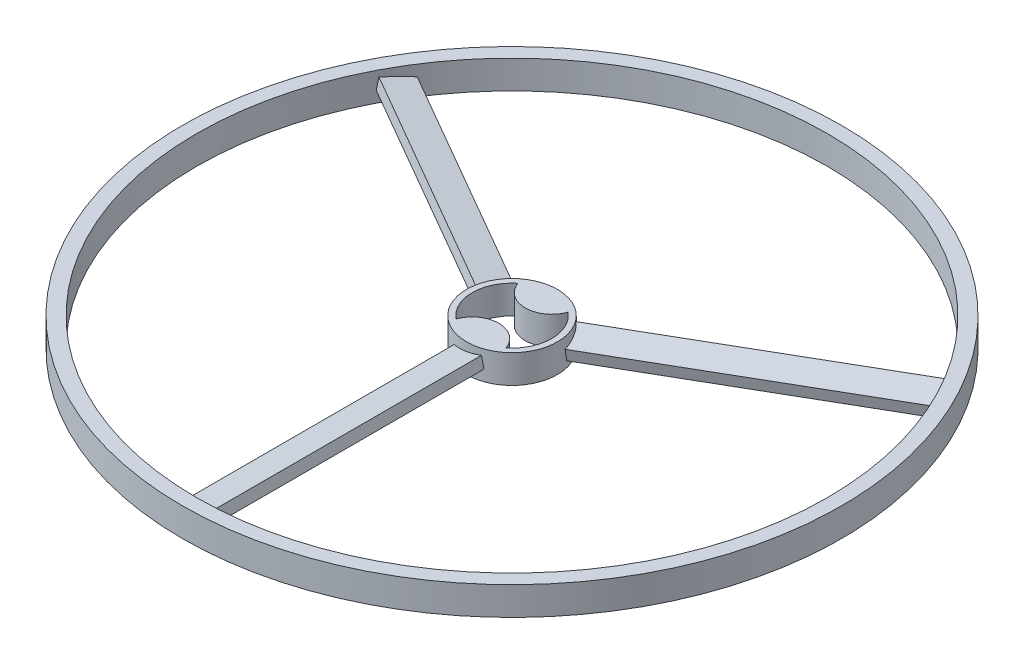
SolidWorks part; units mm, degrees
ref_plane "정면" through (0, 0, 0) normal (0, 0, 1) x (1, 0, 0)
ref_plane "윗면" through (0, 0, 0) normal (0, 1, 0) x (1, 0, 0)
ref_plane "우측면" through (0, 0, 0) normal (1, 0, 0) x (0, 0, -1)
sketch "Sketch1" plane through (0, 0, 0) normal (0, 0, 1) x (1, 0, 0)
  line L0 (-8, 0) -> (8, 0) construction
  line L1 (0, -2.5) -> (0, 2.5) construction
  line L2 (0, 0) -> (2.462, 0.4341) construction
  line L3 (2.2884, 1.4189) -> (2.6357, -0.5507)
  line L4 (2.6357, -0.5507) -> (-2.2884, -1.4189)
  line L5 (-2.2884, -1.4189) -> (-2.6357, 0.5507)
  line L6 (-2.6357, 0.5507) -> (2.2884, 1.4189)
  point P10 (2.462, 0.4341)
  dimension "D1" = 5
  dimension "D2" = 16
  dimension "D3" = 10
  dimension "D4" = 2
  dimension "D5" = 5
  dimension "D6" = 2.5
sketch "Sketch2" plane through (0, 0, 0) normal (0, 1, 0) x (1, 0, 0)
  line L0 (0, 0.9727) -> (0, -14.097) construction
  line L1 (0, 0) -> (-8.1813, 0) construction
  line L2 (-8.1813, 0) -> (8, 0) construction
  circle A0 centre (0, 0) radius 8
  dimension "D1" = 16
sketch "Sketch6" plane through (0, 0, 0) normal (0, 0, 1) x (1, 0, 0)
  line L0 (0, -2.7959) -> (0, 3.0135) construction
sketch "Sketch7" plane through (0, 0, 0) normal (0, 1, 0) x (1, 0, 0)
  circle A0 centre (0, 0) radius 58
  circle A1 centre (0, 0) radius 55.5
  dimension "D1" = 116
  dimension "D2" = 111
extrude "Boss-Extrude4" add sketch "Sketch7" along normal mid plane 5
extrude "Boss-Extrude5" add sketch "Sketch1" along normal up to next
extrude "Boss-Extrude6" add sketch "Sketch2" along normal mid plane 5
pattern_circular "CirPattern5" count 3 over 360 about axis through (0, 0, 0) along (0, 1, 0) of "Boss-Extrude5"
sketch "Sketch9" plane through (0, 2.5, 0) normal (0, 1, 0) x (1, 0, 0)
  line L0 (0, 0) -> (0, -14.2836) construction
  line L1 (0, 0) -> (10.7086, 0) construction
  arc A1 (-4.3998, -5.4444) -> (4.3998, -5.4444) centre (0, -7) cw
  arc A2 (-4.3998, 5.4444) -> (4.3998, 5.4444) centre (0, 7) ccw
  arc A3 (4.3998, -5.4444) -> (4.3998, 5.4444) centre (0, 0) ccw
  arc A4 (-4.3998, -5.4444) -> (-4.3998, 5.4444) centre (0, 0) cw
  dimension "D2" = 4.6667
extrude "Cut-Extrude2" cut sketch "Sketch9" against normal blind 10 contours A4 A1 A3 A2
equation "\"D1@Sketch1\"=0.5"
equation "\"D2@Sketch1\"=1.6"
equation "\"angle\"= 10"
equation "\"D3@Sketch1\"=\"angle\""
equation "\"d\"= 0.2"
equation "\"D4@Sketch1\"=\"d\""
equation "\"w\"= 0.5"
equation "\"D5@Sketch1\"=\"w\""
equation "\"D6@Sketch1\"=\"w\"/2"
equation "\"l\"= 5"
equation "\"n\"= 3"
equation "\"D1@Sketch7\"= \"l\" + \"l\" + 1.6"
equation "\"D2@Sketch7\"=\"l\"+\"l\"+1.6-0.5"
equation "\"D1@CirPattern5\"=\"n\""
equation "\"D2@Sketch9\"=0.46667"
